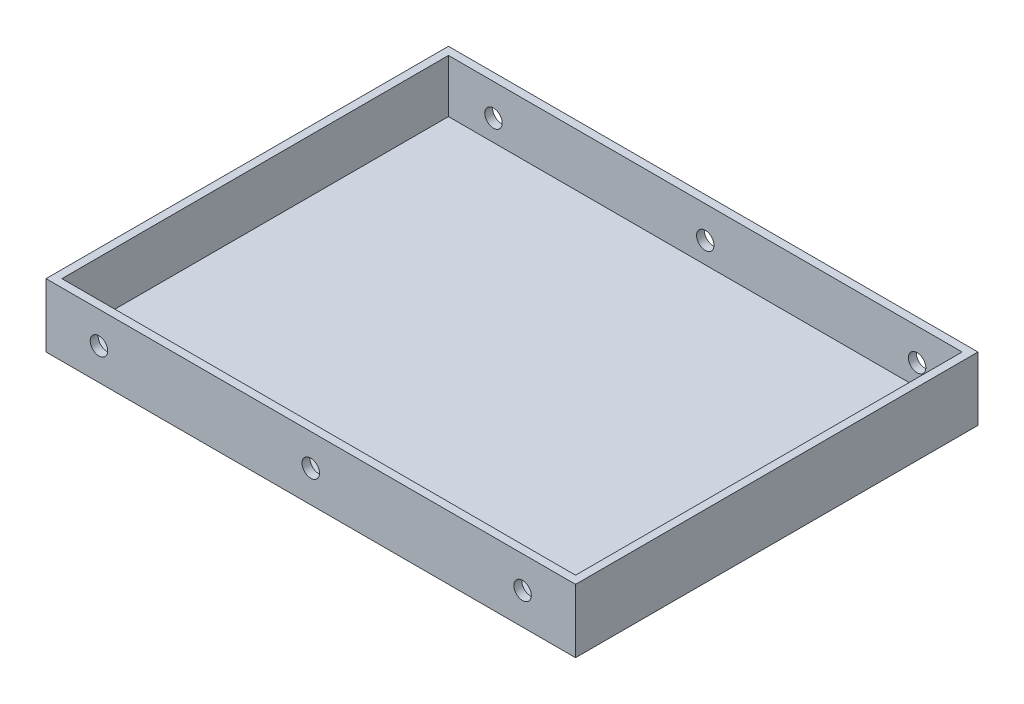
SolidWorks part; units mm, degrees
ref_plane "前视基准面" through (0, 0, 0) normal (0, 0, 1) x (1, 0, 0)
ref_plane "上视基准面" through (0, 0, 0) normal (0, 1, 0) x (1, 0, 0)
ref_plane "右视基准面" through (0, 0, 0) normal (1, 0, 0) x (0, 0, -1)
sketch "草图1" plane through (0, 0, 0) normal (0, 1, 0) x (1, 0, 0)
  line L1 (0, 0) -> (100, 0)
  line L2 (0, 0) -> (0, 76)
  line L3 (0, 76) -> (100, 76)
  line L4 (100, 0) -> (100, 76)
  dimension "D1" = 100
  dimension "D2" = 76
extrude "凸台-拉伸1" add sketch "草图1" along normal blind 12
sketch "草图2" plane through (0, 12, 0) normal (0, 1, 0) x (1, 0, 0)
  line L8 (1.5, 74.5) -> (1.5, 1.5)
  line L9 (1.5, 1.5) -> (98.5, 1.5)
  line L10 (98.5, 1.5) -> (98.5, 74.5)
  line L11 (98.5, 74.5) -> (1.5, 74.5)
  line L12 (1.5, 74.5) -> (1.5, 1.5)
  line L13 (1.5, 1.5) -> (98.5, 1.5)
  line L14 (98.5, 1.5) -> (98.5, 74.5)
  line L15 (98.5, 74.5) -> (1.5, 74.5)
  dimension "D1" = 1.5
extrude "切除-拉伸1" cut sketch "草图2" against normal offset from surface (10 mm away) 2 up to face at (50, 0, -38)
sketch "草图3" plane through (0, 0, -76) normal (0, 0, -1) x (-1, 0, 0)
  line L0 (-100, 6) -> (0, 6) construction
  line L1 (-100, 12) -> (-100, 0) construction
  line L2 (0, 12) -> (0, 0) construction
  line L3 (-50, 6) -> (-50, 17.272) construction
  circle A0 centre (-90, 6) radius 1.65
  circle A1 centre (-10, 6) radius 1.65
  circle A4 centre (-50, 6) radius 1.65
  dimension "D1" = 3.3
  dimension "D2" = 80
extrude "切除-拉伸2" cut sketch "草图3" against normal through all
